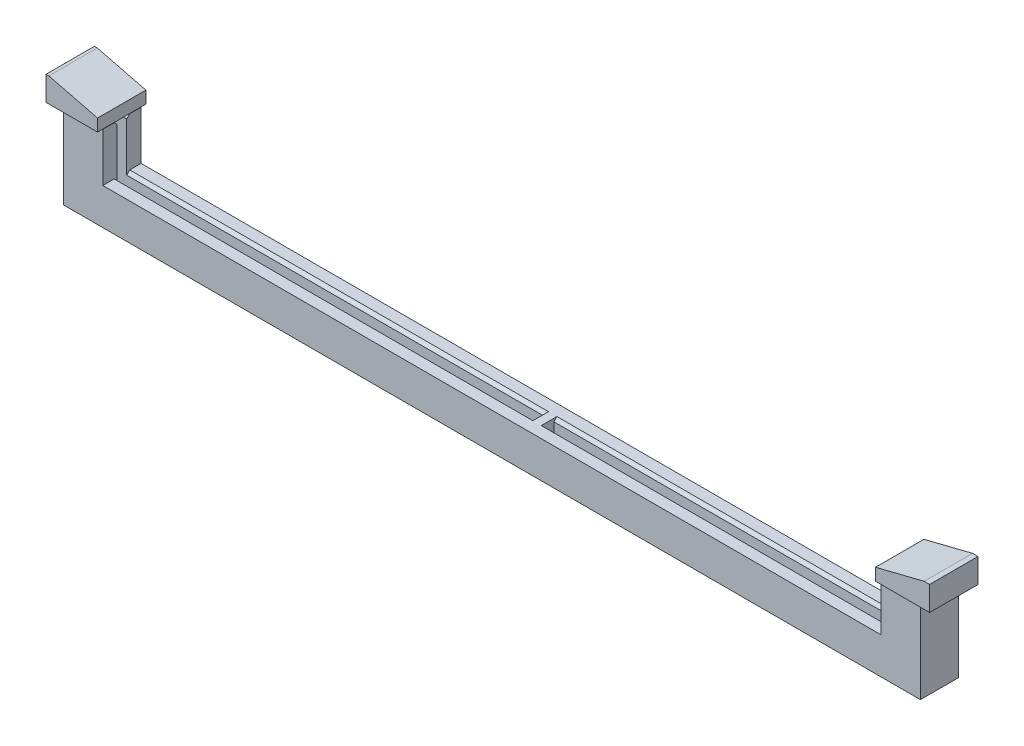
SolidWorks part; units mm, degrees
ref_plane "Front Plane" through (0, 0, 0) normal (0, 0, 1) x (1, 0, 0)
ref_plane "Top Plane" through (0, 0, 0) normal (0, 1, 0) x (1, 0, 0)
ref_plane "Right Plane" through (0, 0, 0) normal (1, 0, 0) x (0, 0, -1)
sketch "Sketch1" plane through (0, 0, 0) normal (0, 1, 0) x (1, 0, 0)
  line L1 (-70.48, -3.15) -> (70.48, -3.15)
  line L2 (-70.48, -3.15) -> (-70.48, 3.15)
  line L3 (-70.48, 3.15) -> (70.48, 3.15)
  line L4 (70.48, -3.15) -> (70.48, 3.15)
  line L5 (-70.48, -3.15) -> (70.48, 3.15) construction
  line L6 (-70.48, 3.15) -> (70.48, -3.15) construction
  point P0 (0, 0)
  dimension "D1" = 6.3
  dimension "D2" = 140.96
extrude "Boss-Extrude1" add sketch "Sketch1" along normal blind 6
sketch "Sketch2" plane through (0, 6, 0) normal (0, 1, 0) x (1, 0, 0)
  line L0 (-70.48, -3.15) -> (70.48, -3.15) construction
  line L1 (70.48, 3.15) -> (63.98, 3.15)
  line L2 (70.48, 3.15) -> (70.48, -3.15)
  line L3 (70.48, -3.15) -> (63.98, -3.15)
  line L4 (63.98, 3.15) -> (63.98, -3.15)
  line L6 (-70.48, 3.15) -> (-63.98, 3.15)
  line L7 (-70.48, 3.15) -> (-70.48, -3.15)
  line L8 (-70.48, -3.15) -> (-63.98, -3.15)
  line L9 (-63.98, 3.15) -> (-63.98, -3.15)
  dimension "D1" = 6.5
  dimension "D2" = 6.5
extrude "Boss-Extrude2" add sketch "Sketch2" along normal blind 8
sketch "Sketch3" plane through (0, 14, 0) normal (0, 1, 0) x (1, 0, 0)
  line L0 (70.48, -3.15) -> (70.48, 3.15) construction
  line L1 (-66.87, 0.785) -> (4.88, 0.785)
  line L2 (-66.87, 0.785) -> (-66.87, -0.785)
  line L3 (-66.87, -0.785) -> (4.88, -0.785)
  line L4 (4.88, 0.785) -> (4.88, -0.785)
  line L5 (66.87, 0.785) -> (6.27, 0.785)
  line L6 (66.87, 0.785) -> (66.87, -0.785)
  line L7 (66.87, -0.785) -> (6.27, -0.785)
  line L8 (6.27, 0.785) -> (6.27, -0.785)
  line L9 (-70.48, 3.15) -> (-70.48, -3.15) construction
  point P10 (70.48, 0)
  point P13 (-70.48, 0)
  dimension "D1" = 3.61
  dimension "D2" = 3.61
  dimension "D3" = 75.36
  dimension "D4" = 64.21
  dimension "D5" = 1.57
  dimension "D6" = 1.57
  dimension "D7" = 0.785
  dimension "D8" = 0.785
extrude "Cut-Extrude1" cut sketch "Sketch3" against normal blind 13
chamfer "Chamfer1" distance 0.5 angle 45 10 edges at (-65.425, 14, 0.785) (-66.87, 14, 0) (-65.425, 14, -0.785) (65.425, 14, 0.785) (66.87, 14, 0) (65.425, 14, -0.785) (35.125, 6, 0.785) (35.125, 6, -0.785) (-29.55, 6, -0.785) (-29.55, 6, 0.785)
sketch "Sketch5" plane through (0, 14, 0) normal (0, 1, 0) x (1, 0, 0)
  line L1 (-72.4897, -3.9795) -> (-64.0209, -3.9795)
  line L2 (-72.4897, -3.9795) -> (-72.4897, 3.9795)
  line L3 (-72.4897, 3.9795) -> (-64.0209, 3.9795)
  line L4 (-64.0209, -3.9795) -> (-64.0209, 3.9795)
  line L5 (-72.4897, -3.9795) -> (-64.0209, 3.9795) construction
  line L6 (-72.4897, 3.9795) -> (-64.0209, -3.9795) construction
  line L7 (63.9285, 3.9795) -> (72.8207, 3.9795)
  line L8 (63.9285, 3.9795) -> (63.9285, -3.9795)
  line L9 (63.9285, -3.9795) -> (72.8207, -3.9795)
  line L10 (72.8207, 3.9795) -> (72.8207, -3.9795)
  line L11 (63.9285, 3.9795) -> (72.8207, -3.9795) construction
  line L12 (63.9285, -3.9795) -> (72.8207, 3.9795) construction
  point P0 (-68.2553, 0)
  point P5 (68.3746, 0)
extrude "Boss-Extrude3" add sketch "Sketch5" along normal blind 4
chamfer "Chamfer2" distance 2 distance2 8 2 edges at (63.9285, 18, 0) (-64.0209, 18, 0)
